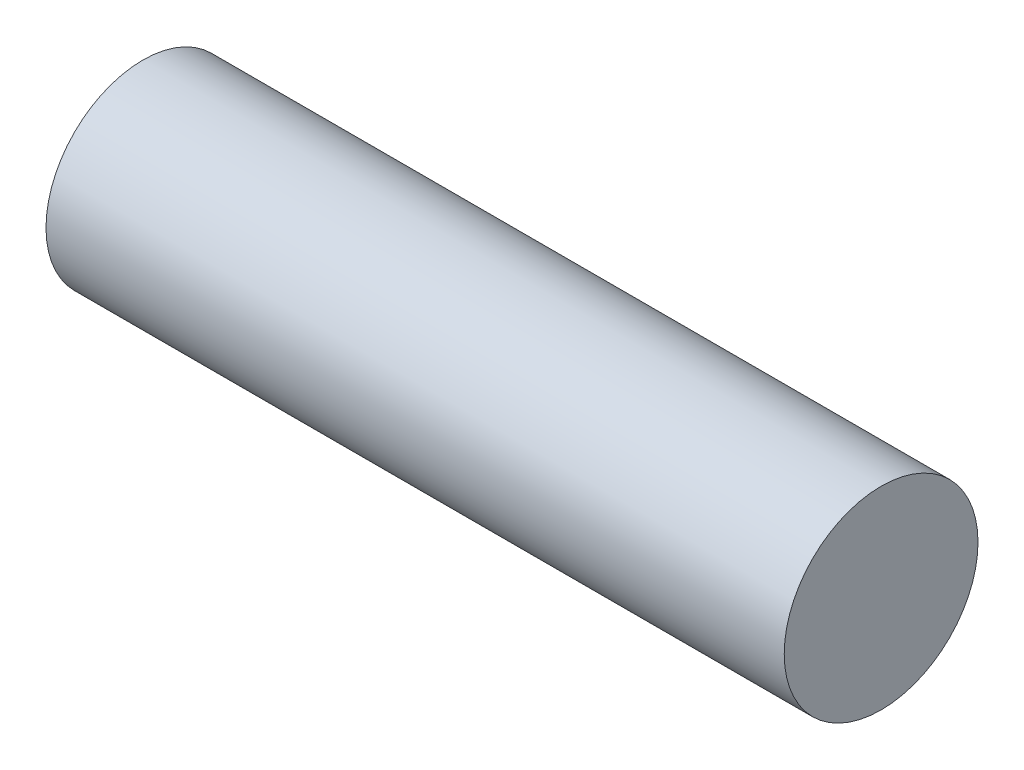
SolidWorks part; units mm, degrees
ref_plane "Front Plane" through (0, 0, 0) normal (0, 0, 1) x (1, 0, 0)
ref_plane "Top Plane" through (0, 0, 0) normal (0, 1, 0) x (1, 0, 0)
ref_plane "Right Plane" through (0, 0, 0) normal (1, 0, 0) x (0, 0, -1)
sketch "Sketch1" plane through (0, 0, 0) normal (1, 0, 0) x (0, 0, -1)
  circle A0 centre (0, 0) radius 10.5
  dimension "D1" = 21
extrude "Boss-Extrude1" add sketch "Sketch1" along normal mid plane 80
